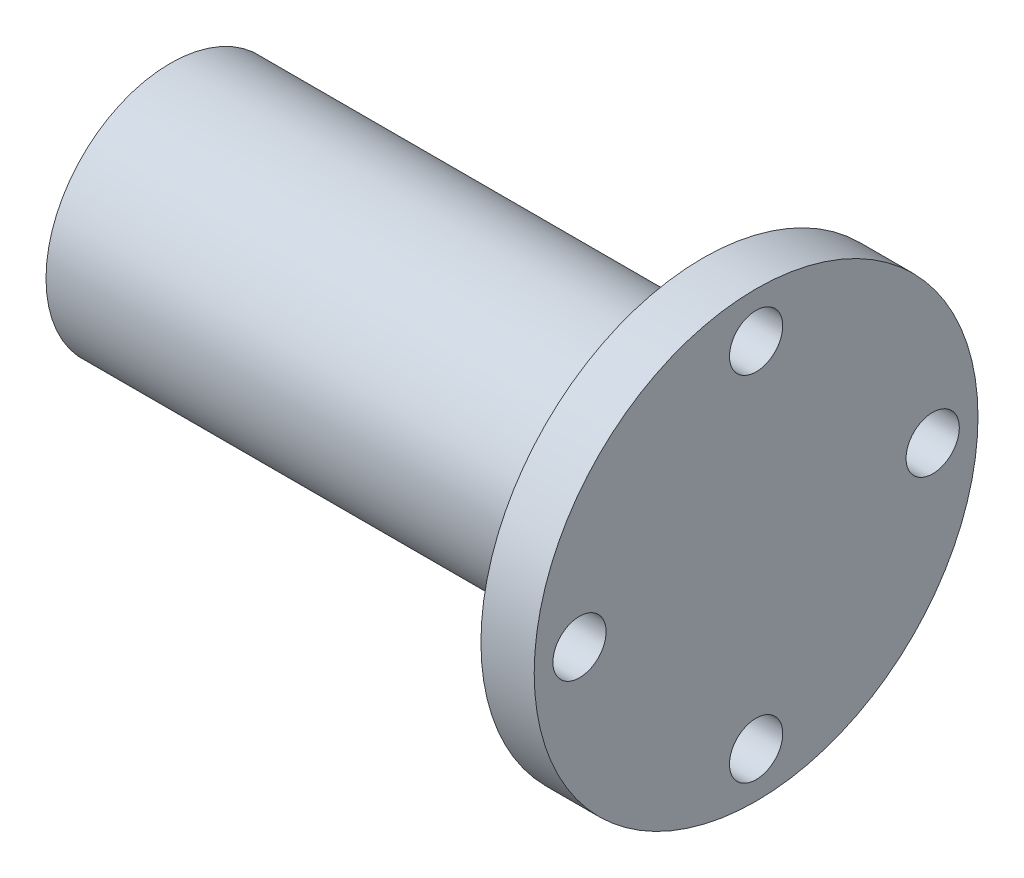
SolidWorks part; units mm, degrees
ref_plane "Front Plane" through (0, 0, 0) normal (0, 0, 1) x (1, 0, 0)
ref_plane "Top Plane" through (0, 0, 0) normal (0, 1, 0) x (1, 0, 0)
ref_plane "Right Plane" through (0, 0, 0) normal (1, 0, 0) x (0, 0, -1)
sketch "Sketch1" plane through (0, 0, 0) normal (1, 0, 0) x (0, 0, -1)
  circle A0 centre (0, 0) radius 7
  dimension "D1" = 14
extrude "Boss-Extrude1" add sketch "Sketch1" against normal blind 30
sketch "Sketch2" plane through (0, 0, 0) normal (1, 0, 0) x (0, 0, -1)
  circle A0 centre (0, 0) radius 12.5
  circle A1 centre (0, 9.9471) radius 1.5
  circle A2 centre (9.9471, 0) radius 1.5
  circle A3 centre (0, -9.9471) radius 1.5
  circle A4 centre (-9.9471, 0) radius 1.5
  circle A5 centre (0, 0) radius 9.9471 construction
  point P12 (0, 0)
  point P13 (0, 0)
  point P14 (0, 0)
  dimension "D1" = 25
  dimension "D2" = 3
extrude "Boss-Extrude2" add sketch "Sketch2" along normal blind 3
